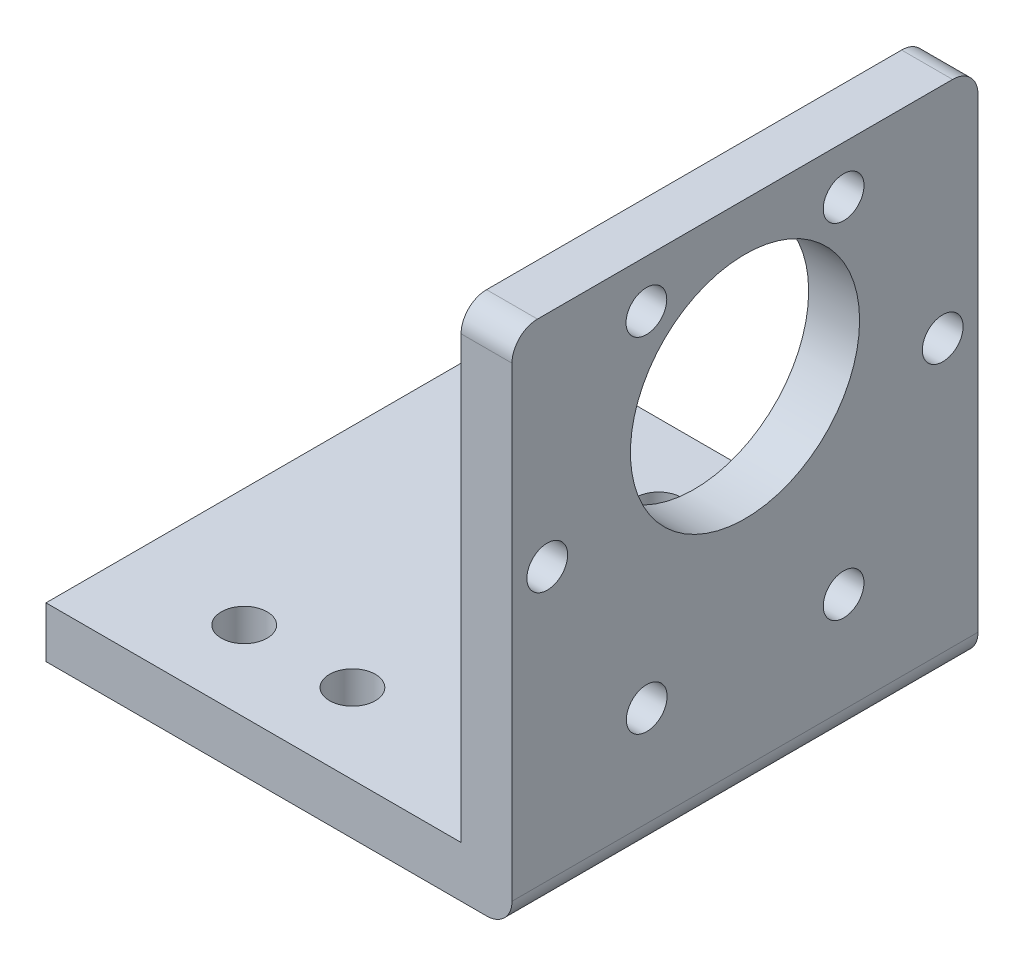
SolidWorks part; units mm, degrees
ref_plane "前视基准面" through (0, 0, 0) normal (0, 0, 1) x (1, 0, 0)
ref_plane "上视基准面" through (0, 0, 0) normal (0, 1, 0) x (1, 0, 0)
ref_plane "右视基准面" through (0, 0, 0) normal (1, 0, 0) x (0, 0, -1)
sketch "草图1" plane through (0, 0, 0) normal (0, 1, 0) x (1, 0, 0)
  line L1 (18.3, -18.3) -> (-18.3, -18.3)
  line L2 (18.3, -18.3) -> (18.3, 18.3)
  line L3 (18.3, 18.3) -> (-18.3, 18.3)
  line L4 (-18.3, -18.3) -> (-18.3, 18.3)
  line L5 (18.3, -18.3) -> (-18.3, 18.3) construction
  line L6 (18.3, 18.3) -> (-18.3, -18.3) construction
  point P0 (0, 0)
  dimension "D1" = 36.6
  dimension "D2" = 36.6
extrude "凸台-拉伸1" add sketch "草图1" along normal blind 40.6
ref_plane "基准面1" through (0, 40.6, 0) normal (0, 1, 0) x (1, 0, 0)
sketch "草图2" plane through (0, 40.6, 0) normal (0, 1, 0) x (1, 0, 0)
  line L0 (-18.3, -18.3) -> (18.3, -18.3) construction
  line L1 (-18.3, 18.3) -> (14.3, 18.3)
  line L2 (-18.3, 18.3) -> (-18.3, -18.3)
  line L3 (-18.3, -18.3) -> (14.3, -18.3)
  line L4 (14.3, 18.3) -> (14.3, -18.3)
  dimension "D1" = 32.6
extrude "切除-拉伸1" cut sketch "草图2" against normal blind 36.6
ref_plane "基准面2" through (18.3, 0, 0) normal (1, 0, 0) x (0, 0, -1)
sketch "草图3" plane through (18.3, 0, 0) normal (1, 0, 0) x (0, 0, -1)
  line L0 (20.13, 40.6) -> (-20.13, 40.6) construction
  line L1 (-18.3, 40.6) -> (18.3, 40.6)
  line L2 (-18.3, 40.6) -> (-18.3, 4)
  line L3 (-18.3, 4) -> (18.3, 4)
  line L4 (18.3, 40.6) -> (18.3, 4)
  line L5 (-18.3, 40.6) -> (-18.3, 0) construction
  line L6 (18.3, 40.6) -> (18.3, 0) construction
  line L7 (0, 40.6) -> (0, 36.8637) construction
  line L8 (0, 36.8637) -> (0, 27.8637) construction
  line L9 (7.7452, 36.8637) -> (-7.7452, 36.8637)
  line L10 (-7.7452, 36.8637) -> (-15.53, 23.3801) construction
  line L11 (7.7452, 36.8637) -> (15.53, 23.3801) construction
  line L12 (-15.53, 23.3801) -> (-7.719, 9.851) construction
  line L13 (-7.719, 9.851) -> (7.7452, 9.851) construction
  line L14 (7.7452, 9.851) -> (15.53, 23.3801) construction
  circle A0 centre (0, 27.8637) radius 9
  circle A1 centre (-7.7452, 36.8637) radius 1.6
  circle A2 centre (7.7452, 36.8637) radius 1.6
  circle A3 centre (-15.53, 23.3801) radius 1.6
  circle A4 centre (15.53, 23.3801) radius 1.6
  circle A5 centre (7.7452, 9.851) radius 1.6
  circle A6 centre (-7.719, 9.851) radius 1.6
  point P10 (0, 40.6)
  point P20 (0, 36.8637)
  dimension "D2" = 120
  dimension "D4" = 18
  dimension "D1" = 36.6
  dimension "D3" = 120
extrude "切除-拉伸5" cut sketch "草图3" against normal blind 36.6
fillet "圆角1" radius 2 1 edges at (18.3, 0, 0)
fillet "圆角2" radius 2 2 edges at (16.3, 40.6, 18.3) (16.3, 40.6, -18.3)
ref_plane "基准面3" through (0, 0, 0) normal (0, -1, 0) x (-1, 0, 0)
sketch "草图7" plane through (0, 0, 0) normal (0, -1, 0) x (-1, 0, 0)
  line L0 (-18.0079, 0) -> (18.3, 0) construction
  line L1 (18.3, 18.3) -> (18.3, -18.3) construction
  circle A0 centre (0.5074, 12.025) radius 1.8
  circle A1 centre (9.0074, 12.025) radius 1.8
  circle A2 centre (9.0074, -12.025) radius 1.8
  circle A3 centre (0.5074, -12.025) radius 1.8
  dimension "D1" = 8.5
  dimension "D2" = 24.05
extrude "切除-拉伸6" cut sketch "草图7" against normal blind 10
